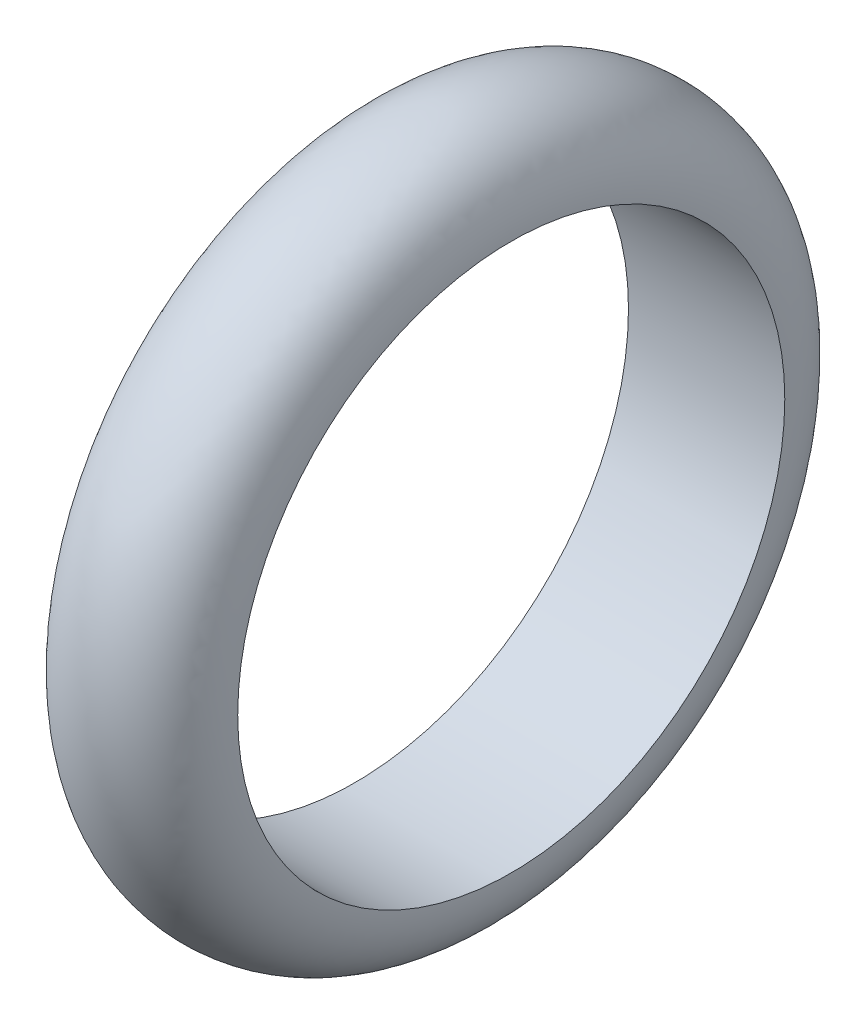
SolidWorks part; units mm, degrees
ref_plane "Front Plane" through (0, 0, 0) normal (0, 0, 1) x (1, 0, 0)
ref_plane "Top Plane" through (0, 0, 0) normal (0, 1, 0) x (1, 0, 0)
ref_plane "Right Plane" through (0, 0, 0) normal (1, 0, 0) x (0, 0, -1)
sketch "Sketch1" plane through (0, 0, 0) normal (0, 1, 0) x (1, 0, 0)
  line L1 (0, 44.45) -> (25.4, 44.45)
  line L2 (0, 0) -> (12.9645, 0) construction
  spline S0 degree 3 poles (0, 44.45) (0, 61.6334) (25.4, 61.6334) (25.4, 44.45) knots 0 0 0 0 1 1 1 1
  dimension "D1" = 25.4
  dimension "D2" = 44.45
revolve "Revolve1" add sketch "Sketch1" angle 360 about L2
